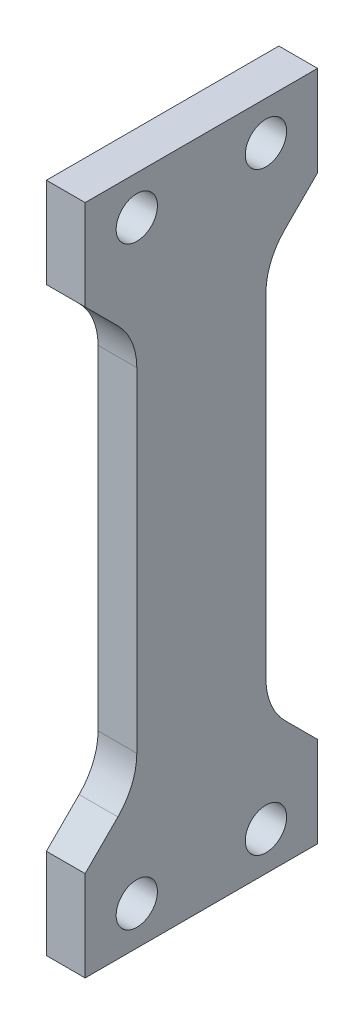
SolidWorks part; units mm, degrees
ref_plane "Front Plane" through (0, 0, 0) normal (0, 0, 1) x (1, 0, 0)
ref_plane "Top Plane" through (0, 0, 0) normal (0, 1, 0) x (1, 0, 0)
ref_plane "Right Plane" through (0, 0, 0) normal (1, 0, 0) x (0, 0, -1)
ref_plane "Plane1" through (120.9887, 0, 0) normal (-1, 0, 0) x (0, -1, 0)
sketch "Sketch1" plane through (120.9887, 0, 0) normal (-1, 0, 0) x (0, -1, 0)
  line L126 (75.0051, 19) -> (75.0051, 37)
  line L127 (75.0051, 37) -> (23.0051, 37)
  line L128 (23.0051, 37) -> (23.0051, 19)
  line L129 (23.0051, 19) -> (75.0051, 19)
  circle A0 centre (26.0051, 33) radius 1.5995
  circle A1 centre (26.0051, 23) radius 1.5995
  circle A2 centre (72.0051, 33) radius 1.5995
  circle A3 centre (72.0051, 23) radius 1.5995
  dimension "D1" = 3.199
  dimension "D2" = 23.0051
  dimension "D3" = 26.0051
  dimension "D4" = 72.0051
  dimension "D5" = 75.0051
  dimension "D6" = 19
  dimension "D7" = 23
  dimension "D8" = 33
  dimension "D9" = 37
extrude "Boss-Extrude1" add sketch "Sketch1" against normal blind 3
sketch "Sketch2" plane through (120.9887, 0, 0) normal (-1, 0, 0) x (0, 0, 1)
  line L0 (28, -23.0051) -> (28, -75.0051) construction
  line L1 (37, -34.0051) -> (33, -34.0051)
  line L2 (37, -34.0051) -> (37, -64.0051)
  line L3 (37, -64.0051) -> (33, -64.0051)
  line L4 (33, -34.0051) -> (33, -64.0051)
  line L5 (37, -23.0051) -> (19, -23.0051) construction
  line L6 (19, -75.0051) -> (37, -75.0051) construction
  line L7 (37, -75.0051) -> (37, -23.0051) construction
  line L8 (33, -34.0051) -> (37, -30.0051)
  line L9 (33, -64.0051) -> (37, -68.0051)
  line L10 (37, -68.0051) -> (37, -64.0051)
  line L11 (37, -30.0051) -> (37, -34.0051)
  line L12 (19, -30.0051) -> (19, -34.0051)
  line L13 (19, -68.0051) -> (19, -64.0051)
  line L14 (23, -64.0051) -> (19, -68.0051)
  line L15 (23, -34.0051) -> (19, -30.0051)
  line L16 (23, -34.0051) -> (23, -64.0051)
  line L17 (19, -64.0051) -> (23, -64.0051)
  line L18 (19, -34.0051) -> (19, -64.0051)
  line L19 (19, -34.0051) -> (23, -34.0051)
  point P10 (37, -49.0051)
  point P13 (37, -49.0051)
  line M10 (19, -23.0051) -> (19, -75.0051)
  line M12 (37, -75.0051) -> (37, -23.0051)
  dimension "D1" = 30
  dimension "D2" = 4
extrude "Cut-Extrude1" cut sketch "Sketch2" against normal through all contours L1 L4 L3 M12 | L8 L1 M12 | L19 L15 M10 | L19 L17 L16 M10 | L17 L14 M10 | L3 L9 M12
fillet "Fillet1" radius 5 4 edges at (122.4887, -64.0051, 23) (122.4887, -64.0051, 33) (122.4887, -34.0051, 33) (122.4887, -34.0051, 23)
